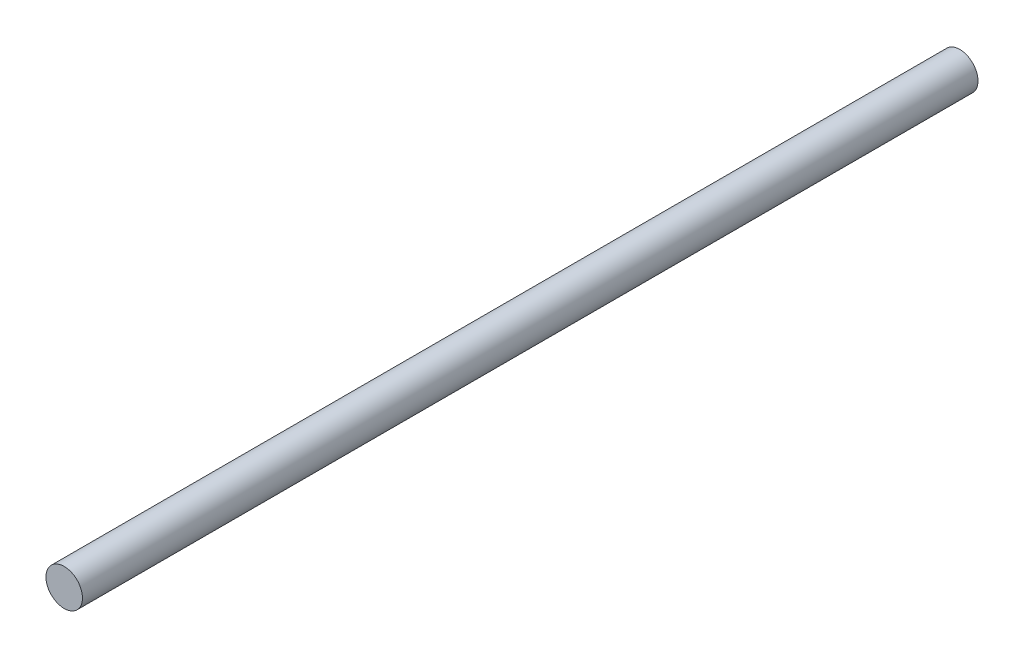
SolidWorks part; units mm, degrees
material "СТ3КП"
ref_plane "Спереди" through (0, 0, 0) normal (0, 0, 1) x (1, 0, 0)
ref_plane "Сверху" through (0, 0, 0) normal (0, 1, 0) x (1, 0, 0)
ref_plane "Справа" through (0, 0, 0) normal (1, 0, 0) x (0, 0, -1)
sketch "Эскиз1" plane through (0, 0, 0) normal (0, 0, 1) x (1, 0, 0)
  circle A0 centre (0, 0) radius 6 construction
  circle A1 centre (0, 0) radius 6
extrude "Бобышка-Вытянуть1" add sketch "Эскиз1" along normal blind 147.3
mirror "Зеркальное отражение1" about plane through (0, 0, 0) normal (0, 0, 1) of bodies 103
equation "\"D1@Бобышка-Вытянуть1\"=97.3+50"
